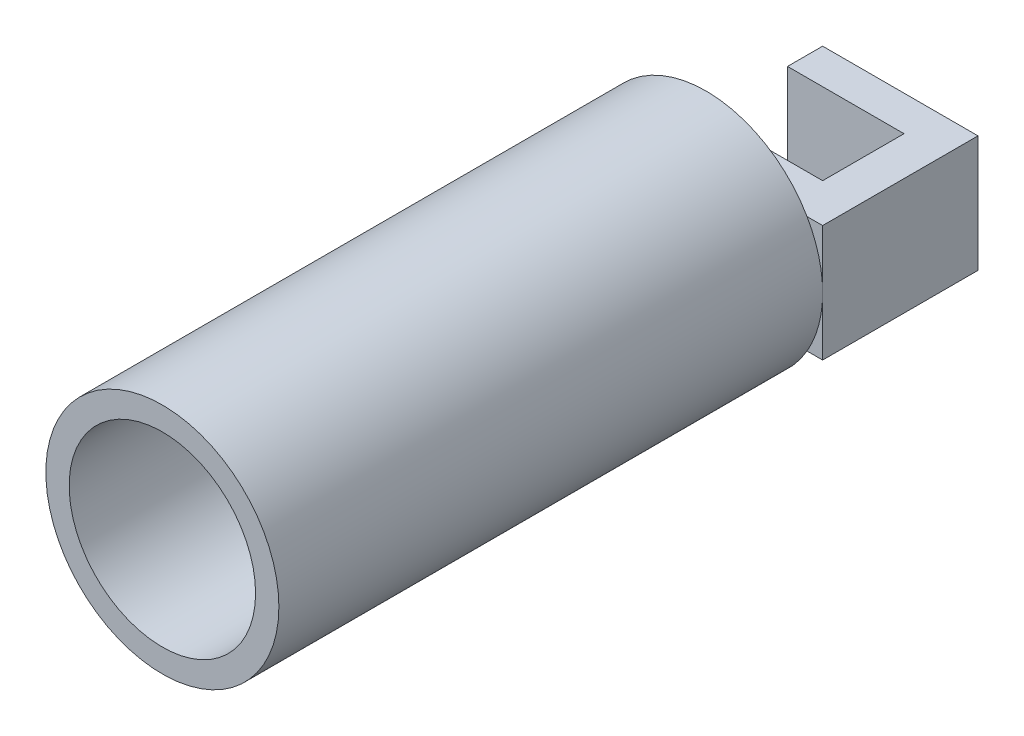
SolidWorks part; units mm, degrees
ref_plane "Plan de face" through (0, 0, 0) normal (0, 0, 1) x (1, 0, 0)
ref_plane "Plan de dessus" through (0, 0, 0) normal (0, 1, 0) x (1, 0, 0)
ref_plane "Plan de droite" through (0, 0, 0) normal (1, 0, 0) x (0, 0, -1)
sketch "Esquisse1" plane through (0, 0, 0) normal (0, 0, 1) x (1, 0, 0)
  circle A0 centre (0, 0) radius 15
  dimension "D1" = 30
extrude "Boss.-Extru.1" add sketch "Esquisse1" along normal blind 70 contours A0
sketch "Esquisse2" plane through (0, 0, 70) normal (0, 0, 1) x (1, 0, 0)
  circle A0 centre (0, 0) radius 12
  circle A1 centre (0, 0) radius 15 construction
  dimension "D1" = 3
extrude "Enlèv. mat.-Extru.1" cut sketch "Esquisse2" against normal blind 65 contours A0
sketch "Esquisse3" plane through (0, 0, 0) normal (0, 0, -1) x (-1, 0, 0)
  line L5 (-5, 7.5) -> (0, 7.5)
  line L6 (-5, 7.5) -> (-5, -7.5)
  line L7 (-5, -7.5) -> (0, -7.5)
  line L8 (0, 7.5) -> (0, -7.5)
  dimension "D1" = 5
  dimension "D2" = 0
  dimension "D3" = 15
  dimension "D4" = 7.5
extrude "Boss.-Extru.2" add sketch "Esquisse3" along normal blind 5
sketch "Esquisse12" plane through (5, 0, 0) normal (1, 0, 0) x (0, 0, -1)
  line L0 (0, 7.5) -> (5, 7.5)
  line L1 (5, 7.5) -> (5, -7.5)
  line L2 (5, -7.5) -> (0, -7.5)
  line L3 (0, -7.5) -> (0, 7.5)
extrude "Boss.-Extru.6" add sketch "Esquisse12" along normal blind 10
sketch "Esquisse13" plane through (0, 0, -5) normal (0, 0, -1) x (-1, 0, 0)
  line L0 (-15, 7.5) -> (-10, 7.5)
  line L1 (0, 7.5) -> (-15, 7.5) construction
  line L2 (-10, 7.5) -> (-10, -7.5)
  line L3 (-15, -7.5) -> (0, -7.5) construction
  line L4 (-10, -7.5) -> (-15, -7.5)
  line L5 (-15, -7.5) -> (-15, 7.5)
  dimension "D1" = 5
extrude "Boss.-Extru.7" add sketch "Esquisse13" along normal blind 15
sketch "Esquisse14" plane through (10, 0, 0) normal (-1, 0, 0) x (0, 0, 1)
  line L0 (-20, 7.5) -> (-15.4792, 7.5)
  line L1 (-20, 7.5) -> (-5, 7.5) construction
  line L2 (-15.4792, 7.5) -> (-15.4792, -7.5)
  line L3 (-20, -7.5) -> (-5, -7.5) construction
  line L4 (-15.4792, -7.5) -> (-20, -7.5)
  line L5 (-20, -7.5) -> (-20, 7.5)
extrude "Boss.-Extru.8" add sketch "Esquisse14" along normal blind 15
equation "\"taille\"= 3mm"
